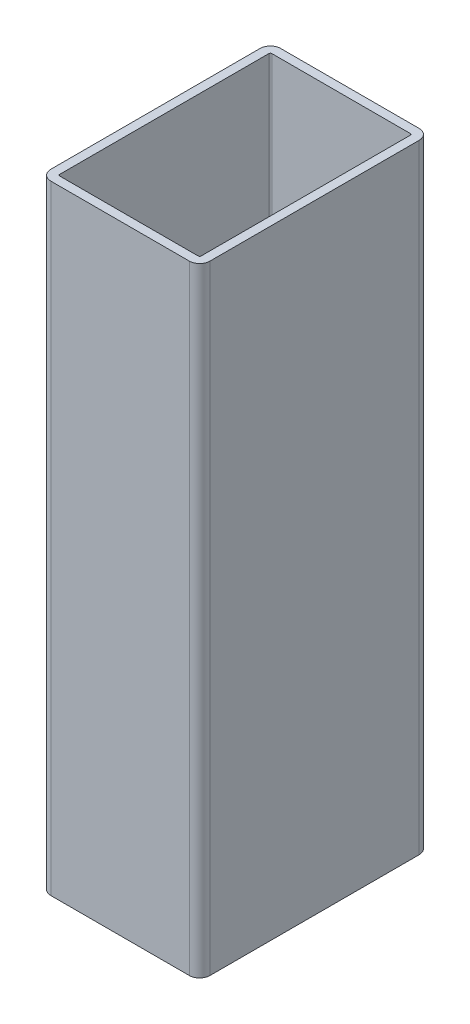
SolidWorks part; units mm, degrees
other "Weld Folder"
ref_plane "Front Plane" through (0, 0, 0) normal (0, 0, 1) x (1, 0, 0)
ref_plane "Top Plane" through (0, 0, 0) normal (0, 1, 0) x (1, 0, 0)
ref_plane "Right Plane" through (0, 0, 0) normal (1, 0, 0) x (0, 0, -1)
sketch "Sketch1" plane through (0, 0, 0) normal (0, 0, 1) x (1, 0, 0)
  line L0 (0, 0) -> (0, 700)
  dimension "D1" = 700
other "Rhs RHS90X50X5(1)"
ref_plane "Plane1" through (0, 0, 0) normal (0, 1, 0) x (-1, 0, 0)
sketch "Sketch11" plane through (0, 0, 0) normal (0, 1, 0) x (-1, 0, 0)
  line L0 (-78.3333, -120) -> (78.3333, -120)
  line L1 (-80, -118.3333) -> (-80, 118.3333)
  line L2 (78.3333, 120) -> (-78.3333, 120)
  line L3 (80, 118.3333) -> (80, -118.3333)
  line L4 (-78.3333, -130) -> (78.3333, -130)
  line L5 (-90, -118.3333) -> (-90, 118.3333)
  line L6 (78.3333, 130) -> (-78.3333, 130)
  line L7 (90, 118.3333) -> (90, -118.3333)
  line L8 (-90, 0) -> (-80, 0) construction
  line L9 (-80, 0) -> (80, 0) construction
  line L10 (80, 0) -> (90, 0) construction
  line L11 (0, 130) -> (0, 120) construction
  line L12 (0, 120) -> (0, -120) construction
  line L13 (0, -120) -> (0, -130) construction
  arc A0 (90, 118.3333) -> (78.3333, 130) centre (78.3333, 118.3333) ccw
  arc A1 (78.3333, -130) -> (90, -118.3333) centre (78.3333, -118.3333) ccw
  arc A2 (-90, -118.3333) -> (-78.3333, -130) centre (-78.3333, -118.3333) ccw
  arc A3 (-78.3333, 130) -> (-90, 118.3333) centre (-78.3333, 118.3333) ccw
  arc A4 (-78.3333, 120) -> (-80, 118.3333) centre (-78.3333, 118.3333) ccw
  arc A5 (80, 118.3333) -> (78.3333, 120) centre (78.3333, 118.3333) ccw
  arc A6 (78.3333, -120) -> (80, -118.3333) centre (78.3333, -118.3333) ccw
  arc A7 (-80, -118.3333) -> (-78.3333, -120) centre (-78.3333, -118.3333) ccw
  point P6 (90, -130)
  point P33 (-90, -130)
  point P35 (-90, 130)
  point P36 (90, 130)
  point P37 (0, 0)
  point P38 (0, 0)
  dimension "Thickness" = 10
  dimension "V_leg" = 260
  dimension "H_leg" = 180
sketch "Sketch12" plane through (0, 0, 0) normal (0, -1, 0) x (1, 0, 0)
  line L0 (90, 118.3333) -> (90, -118.3333) construction
  line L1 (78.3333, -130) -> (-78.3333, -130) construction
  line L2 (-90, -118.3333) -> (-90, 118.3333) construction
  line L3 (-78.3333, 130) -> (78.3333, 130) construction
  line L4 (90, 118.3333) -> (90, -118.3333)
  line L5 (78.3333, -130) -> (-78.3333, -130)
  line L6 (-90, -118.3333) -> (-90, 118.3333)
  line L7 (-78.3333, 130) -> (78.3333, 130)
  arc A0 (90, 118.3333) -> (78.3333, 130) centre (78.3333, 118.3333) ccw construction
  arc A1 (78.3333, -130) -> (90, -118.3333) centre (78.3333, -118.3333) ccw construction
  arc A2 (-90, -118.3333) -> (-78.3333, -130) centre (-78.3333, -118.3333) ccw construction
  arc A3 (-78.3333, 130) -> (-90, 118.3333) centre (-78.3333, 118.3333) ccw construction
  arc A4 (90, 118.3333) -> (78.3333, 130) centre (78.3333, 118.3333) ccw
  arc A5 (78.3333, -130) -> (90, -118.3333) centre (78.3333, -118.3333) ccw
  arc A6 (-90, -118.3333) -> (-78.3333, -130) centre (-78.3333, -118.3333) ccw
  arc A7 (-78.3333, 130) -> (-90, 118.3333) centre (-78.3333, 118.3333) ccw
